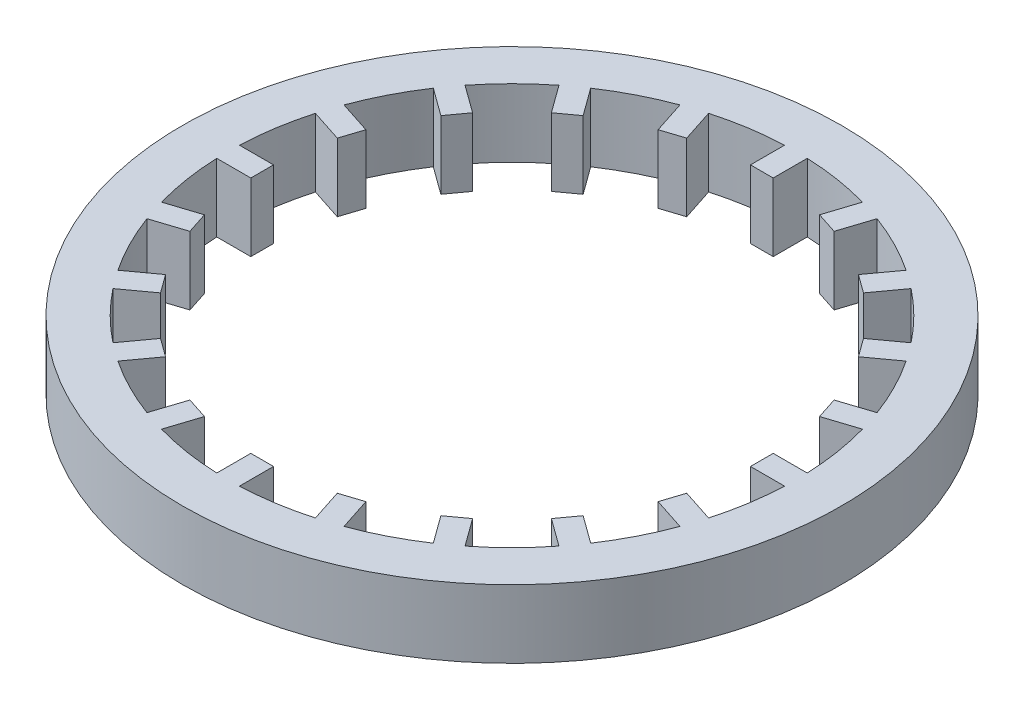
SolidWorks part; units mm, degrees
ref_plane "前基準面" through (0, 0, 0) normal (0, 0, 1) x (1, 0, 0)
ref_plane "上基準面" through (0, 0, 0) normal (0, 1, 0) x (1, 0, 0)
ref_plane "右基準面" through (0, 0, 0) normal (1, 0, 0) x (0, 0, -1)
sketch "草圖2" plane through (0, 0, 0) normal (0, 1, 0) x (1, 0, 0)
  line L0 (0, 131.5156) -> (0, -142.5058) construction
  line L1 (-109.7369, 0) -> (170.3475, 0) construction
  line L2 (29.2366, 106.1613) -> (33.8718, 120.4271)
  line L3 (5, 110) -> (-5, 110)
  line L4 (5, 110) -> (5, 125)
  line L6 (-5, 110) -> (-5, 125)
  line L7 (0, 104.7477) -> (0, 110) construction
  line L8 (5, 117.5) -> (-5, 117.5) construction
  line L9 (38.7472, 103.0711) -> (43.3824, 117.337)
  line L10 (38.7472, 103.0711) -> (29.2366, 106.1613)
  line L11 (60.6113, 91.9308) -> (69.4281, 104.0661)
  line L12 (68.7015, 86.0529) -> (77.5182, 98.1882)
  line L13 (68.7015, 86.0529) -> (60.6113, 91.9308)
  line L14 (86.0529, 68.7015) -> (98.1882, 77.5182)
  line L15 (91.9308, 60.6113) -> (104.0661, 69.4281)
  line L16 (91.9308, 60.6113) -> (86.0529, 68.7015)
  line L17 (103.0711, 38.7472) -> (117.337, 43.3824)
  line L18 (106.1613, 29.2366) -> (120.4271, 33.8718)
  line L19 (106.1613, 29.2366) -> (103.0711, 38.7472)
  line L20 (110, 5) -> (125, 5)
  line L21 (110, -5) -> (125, -5)
  line L22 (110, -5) -> (110, 5)
  line L23 (106.1613, -29.2366) -> (120.4271, -33.8718)
  line L24 (103.0711, -38.7472) -> (117.337, -43.3824)
  line L25 (103.0711, -38.7472) -> (106.1613, -29.2366)
  line L26 (91.9308, -60.6113) -> (104.0661, -69.4281)
  line L27 (86.0529, -68.7015) -> (98.1882, -77.5182)
  line L28 (86.0529, -68.7015) -> (91.9308, -60.6113)
  line L29 (68.7015, -86.0529) -> (77.5182, -98.1882)
  line L30 (60.6113, -91.9308) -> (69.4281, -104.0661)
  line L31 (60.6113, -91.9308) -> (68.7015, -86.0529)
  line L32 (38.7472, -103.0711) -> (43.3824, -117.337)
  line L33 (29.2366, -106.1613) -> (33.8718, -120.4271)
  line L34 (29.2366, -106.1613) -> (38.7472, -103.0711)
  line L35 (5, -110) -> (5, -125)
  line L36 (-5, -110) -> (-5, -125)
  line L37 (-5, -110) -> (5, -110)
  line L38 (-29.2366, -106.1613) -> (-33.8718, -120.4271)
  line L39 (-38.7472, -103.0711) -> (-43.3824, -117.337)
  line L40 (-38.7472, -103.0711) -> (-29.2366, -106.1613)
  line L41 (-60.6113, -91.9308) -> (-69.4281, -104.0661)
  line L42 (-68.7015, -86.0529) -> (-77.5182, -98.1882)
  line L43 (-68.7015, -86.0529) -> (-60.6113, -91.9308)
  line L44 (-86.0529, -68.7015) -> (-98.1882, -77.5182)
  line L45 (-91.9308, -60.6113) -> (-104.0661, -69.4281)
  line L46 (-91.9308, -60.6113) -> (-86.0529, -68.7015)
  line L47 (-103.0711, -38.7472) -> (-117.337, -43.3824)
  line L48 (-106.1613, -29.2366) -> (-120.4271, -33.8718)
  line L49 (-106.1613, -29.2366) -> (-103.0711, -38.7472)
  line L50 (-110, -5) -> (-125, -5)
  line L51 (-110, 5) -> (-125, 5)
  line L52 (-110, 5) -> (-110, -5)
  line L53 (-106.1613, 29.2366) -> (-120.4271, 33.8718)
  line L54 (-103.0711, 38.7472) -> (-117.337, 43.3824)
  line L55 (-103.0711, 38.7472) -> (-106.1613, 29.2366)
  line L56 (-91.9308, 60.6113) -> (-104.0661, 69.4281)
  line L57 (-86.0529, 68.7015) -> (-98.1882, 77.5182)
  line L58 (-86.0529, 68.7015) -> (-91.9308, 60.6113)
  line L59 (-68.7015, 86.0529) -> (-77.5182, 98.1882)
  line L60 (-60.6113, 91.9308) -> (-69.4281, 104.0661)
  line L61 (-60.6113, 91.9308) -> (-68.7015, 86.0529)
  line L62 (-38.7472, 103.0711) -> (-43.3824, 117.337)
  line L63 (-29.2366, 106.1613) -> (-33.8718, 120.4271)
  line L64 (-29.2366, 106.1613) -> (-38.7472, 103.0711)
  circle A0 centre (0, 0) radius 145.1
  arc A1 (-5, 125) -> (-33.8718, 120.4271) centre (0, 0) ccw
  circle A2 centre (0, 0) radius 125.1 construction
  arc A3 (-43.3824, 117.337) -> (-69.4281, 104.0661) centre (0, 0) ccw
  arc A4 (-77.5182, 98.1882) -> (-98.1882, 77.5182) centre (0, 0) ccw
  arc A5 (-104.0661, 69.4281) -> (-117.337, 43.3824) centre (0, 0) ccw
  arc A6 (-120.4271, 33.8718) -> (-125, 5) centre (0, 0) ccw
  arc A7 (-125, -5) -> (-120.4271, -33.8718) centre (0, 0) ccw
  arc A8 (-117.337, -43.3824) -> (-104.0661, -69.4281) centre (0, 0) ccw
  arc A9 (-98.1882, -77.5182) -> (-77.5182, -98.1882) centre (0, 0) ccw
  arc A10 (-69.4281, -104.0661) -> (-43.3824, -117.337) centre (0, 0) ccw
  arc A11 (-33.8718, -120.4271) -> (-5, -125) centre (0, 0) ccw
  arc A12 (5, -125) -> (33.8718, -120.4271) centre (0, 0) ccw
  arc A13 (43.3824, -117.337) -> (69.4281, -104.0661) centre (0, 0) ccw
  arc A14 (77.5182, -98.1882) -> (98.1882, -77.5182) centre (0, 0) ccw
  arc A15 (104.0661, -69.4281) -> (117.337, -43.3824) centre (0, 0) ccw
  arc A16 (120.4271, -33.8718) -> (125, -5) centre (0, 0) ccw
  arc A17 (125, 5) -> (120.4271, 33.8718) centre (0, 0) ccw
  arc A18 (117.337, 43.3824) -> (104.0661, 69.4281) centre (0, 0) ccw
  arc A19 (98.1882, 77.5182) -> (77.5182, 98.1882) centre (0, 0) ccw
  arc A20 (33.8718, 120.4271) -> (5, 125) centre (0, 0) ccw
  arc A21 (69.4281, 104.0661) -> (43.3824, 117.337) centre (0, 0) ccw
  point P9 (0, 117.5)
  point P94 (0, 0)
  dimension "D1" = 20
  dimension "D4" = 250
  dimension "D2" = 10
  dimension "D3" = 15
  dimension "D5" = 20
extrude "填料-伸長1" add sketch "草圖2" along normal blind 30
